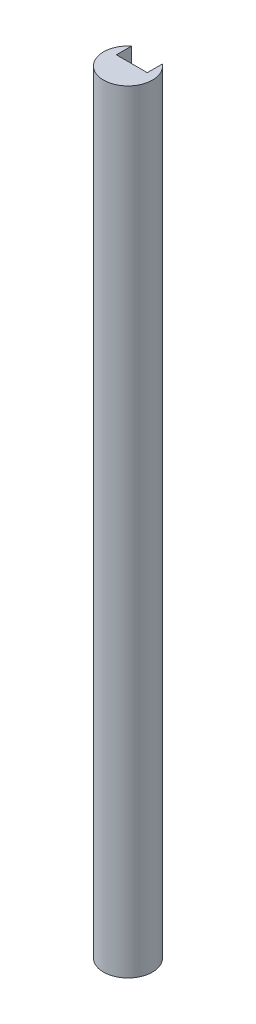
SolidWorks part; units mm, degrees
ref_plane "Front Plane" through (0, 0, 0) normal (0, 0, 1) x (1, 0, 0)
ref_plane "Top Plane" through (0, 0, 0) normal (0, 1, 0) x (1, 0, 0)
ref_plane "Right Plane" through (0, 0, 0) normal (1, 0, 0) x (0, 0, -1)
sketch "Sketch1" plane through (0, 0, 0) normal (0, 1, 0) x (1, 0, 0)
  line L2 (-1.524, 1.8708) -> (-1.524, 0.381)
  line L3 (1.524, 1.8708) -> (1.524, 0.381)
  line L4 (-1.524, 0.381) -> (1.524, 0.381)
  arc A0 (-1.524, 1.8708) -> (1.524, 1.8708) centre (0, 0) ccw
  dimension "D1" = 4.826
extrude "Boss-Extrude2" add sketch "Sketch1" along normal blind 76.2 contours A0 L3 L4 L2
